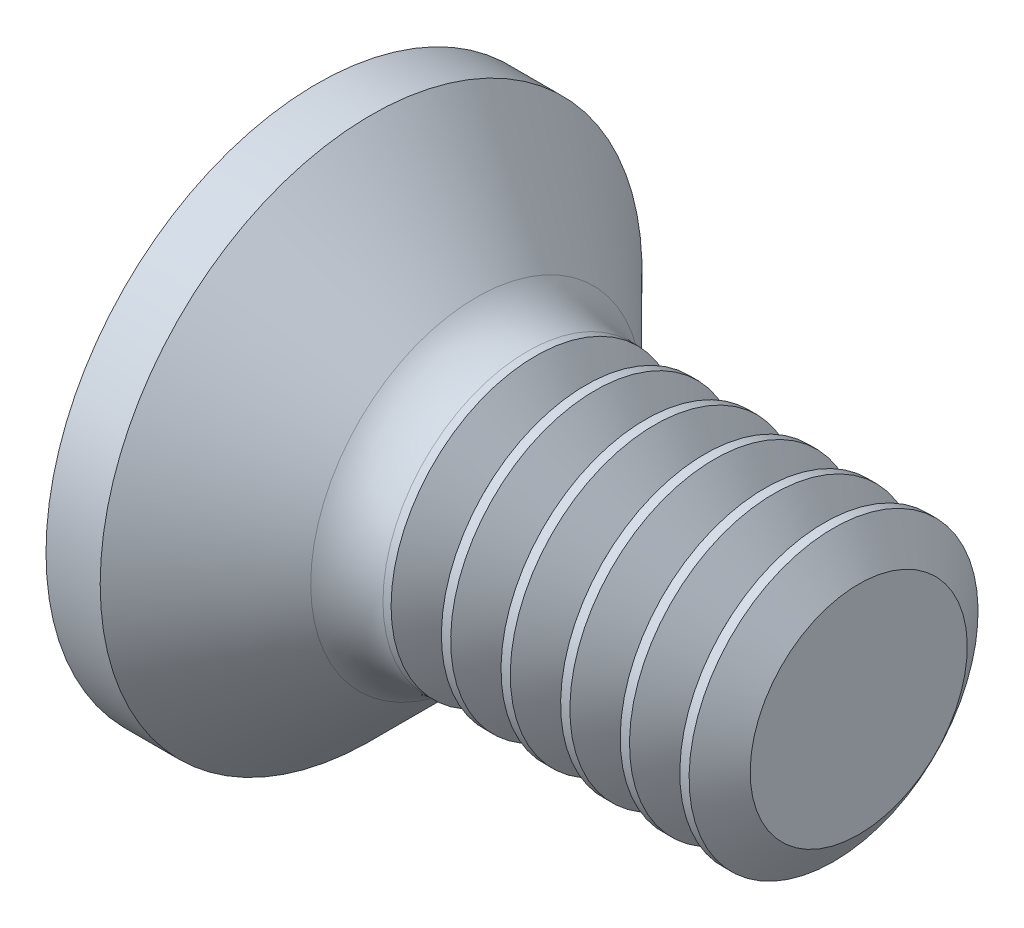
SolidWorks part; units mm, degrees
revolve "Base-Revolve" add sketch "BodySke"
sketch "BodySke" plane through (0, 0, 0) normal (0, 0, 1) x (1, 0, 0)
  line L0 (0, 0) -> (0, 1.5)
  line L1 (0, 1.5) -> (0.3, 1.5)
  line L2 (1, 0.8) -> (3, 0.8)
  line L3 (3, 0.8) -> (3, 0)
  line L4 (3, 0) -> (0, 0)
  line L5 (-6.35, 0) -> (82.55, 0) construction
  line L6 (1, -0.8) -> (3, -0.8) construction
  line L7 (0.3, -1.5) -> (1, -0.8) construction
  line L8 (0.3, 1.5) -> (1, 0.8)
  line L9 (0, -1.5) -> (0.3, -1.5) construction
  line L10 (1.35, 2.3875) -> (1.35, -7.1375) construction
  line L11 (0, 6.35) -> (0, -3.175) construction
  dimension "Diameter" = 1.6
  dimension "Length" = 3
  dimension "Head_ht" = 1
  dimension "Head_dia" = 3
  dimension "Head_ang" = 90
  dimension "D6" = 0.3
  dimension "Advance" = 0.35
  dimension "Thread_nom" = 3
cosmetic thread "ThreadCosmetic" [suppressed]
fillet "Fillet1" radius 0.4 1 edges at (1, 0, 0.8)
ref_plane "Plane1" through (0, 0, 0) normal (0, 0, 1) x (1, 0, 0)
ref_plane "Plane2" through (0, 0, 0) normal (0, 1, 0) x (1, 0, 0)
ref_plane "Plane3" through (0, 0, 0) normal (1, 0, 0) x (0, 0, -1)
sketch "Sketch3" plane through (0, 0, 0) normal (-1, 0, 0) x (0, 0, 1)
  line L0 (-0.24, 0.8) -> (0.24, 0.8)
  line L1 (0.24, 0.8) -> (0.24, -0.8)
  line L2 (0.24, -0.8) -> (-0.24, -0.8)
  line L3 (-0.24, -0.8) -> (-0.24, 0.8)
  dimension "Cross_dia" = 1.6
  dimension "Cross_width" = 0.48
  dimension "D1" = 0.8
  dimension "D2" = 0.24
ref_plane "Plane4" through (0.95, 0, 0) normal (-1, 0, 0) x (0, 0, 1)
sketch "Sketch4" plane through (0.95, 0, 0) normal (-1, 0, 0) x (0, 0, 1)
  line L0 (-0.24, 0.3263) -> (0.24, 0.3263)
  line L3 (0.24, 0.3263) -> (0.24, -0.3263)
  line L4 (0.24, -0.3263) -> (-0.24, -0.3263)
  line L5 (-0.24, -0.3263) -> (-0.24, 0.3263)
  dimension "D2" = 0.6527
  dimension "D1" = 0.48
  dimension "D4" = 0.3263
  dimension "D3" = 0.24
loft "Recess" cut profiles "Sketch3", "Sketch4"
pattern_circular "RecPat" count 2 every 90 about axis through (0, 0, 0) along (1, 0, 0) of "Recess"
sketch "RecCorSke" plane through (0, 0, 0) normal (0, 0, 1) x (1, 0, 0)
  line L0 (-3.175, 0) -> (15.875, 0) construction
  line L2 (0, 0) -> (0, 0.4219)
  line L3 (0, 0.4219) -> (0.95, 0.3555)
  line L4 (0.95, 0.3555) -> (1.0655, 0)
  line L5 (1.0655, 0) -> (0, 0)
  dimension "Diameter" = 0.711
  dimension "Depth" = 0.95
  dimension "Draft_angle" = 4
  dimension "Bottom_angle" = 18
revolve "RecessCore" cut sketch "RecCorSke" angle 360 about L0
sketch "ThdSchSke" plane through (0, 0, 0) normal (0, 0, 1) x (1, 0, 0)
  line L0 (1.35, -0.601) -> (1.2107, -0.8)
  line L1 (1.35, -0.601) -> (1.4893, -0.8)
  line L2 (1.4893, -0.8) -> (1.4893, -1)
  line L3 (-3.175, 0) -> (5.1513, 0) construction
  line L5 (1.4893, -1) -> (1.2107, -1)
  line L6 (1.2107, -1) -> (1.2107, -0.8)
  line L7 (0, 1.5) -> (0, -1.5) construction
  dimension "Diameter" = 1.6
  dimension "Thread_minor" = 1.202
  dimension "Start" = 1.35
revolve "ThreadSchematic" cut sketch "ThdSchSke" angle 360 about L3
pattern_linear "ThdSchPat" count 6 spacing 0.33 along (1, 0, 0) of "ThreadSchematic"
equation "\"D1@Sketch3\" = \"Cross_dia@Sketch3\" / 2"
equation "\"D2@Sketch3\" = \"Cross_width@Sketch3\" / 2"
equation "\"Depth@RecCorSke\" = \"Cross_depth@Plane4\""
equation "\"D1@Sketch4\" = \"Cross_width@Sketch3\""
equation "\"D2@Sketch4\" = \"Cross_dia@Sketch3\" - 2.0 * \"Cross_depth@Plane4\" * tan(26.5  * 0.017453292)"
equation "\"D3@Sketch4\" = \"D1@Sketch4\" / 2"
equation "\"D4@Sketch4\" = \"D2@Sketch4\" / 2"
equation "\"Thread_length@ThreadCosmetic\" = ((sgn( (\"Length@BodySke\" - \"Advance@BodySke\" * 1.0 - \"Head_ht@BodySke\" ) - \"Thread_nom@BodySke\" )-1)*( (\"Length@BodySke\" - \"Advance@BodySke\" * 1.0 - \"Head_ht@BodySke\" ) - \"Thread_nom@BodySke\" ))/-2+ \"Thread_nom@BodySke\""
equation "\"Thread_minor@ThdSchSke\" = \"Thread_minor@ThreadCosmetic\""
equation "\"Diameter@ThdSchSke\" = \"Diameter@BodySke\""
equation "\"Overcut@ThdSchSke\" = \"Diameter@BodySke\" * 1.25"
equation "\"Start@ThdSchSke\" = 0.000001 + \"Length@BodySke\" - \"Thread_length@ThreadCosmetic\"  '---Countersunk---"
equation "\"Num_threads@ThdSchPat\" = int( \"Thread_length@ThreadCosmetic\" / \"Advance@BodySke\" + 0.999 )  + 1"
equation "\"Advance@ThdSchPat\" = \"Thread_length@ThreadCosmetic\" /  (\"Num_threads@ThdSchPat\" - 1) 'relax it"
